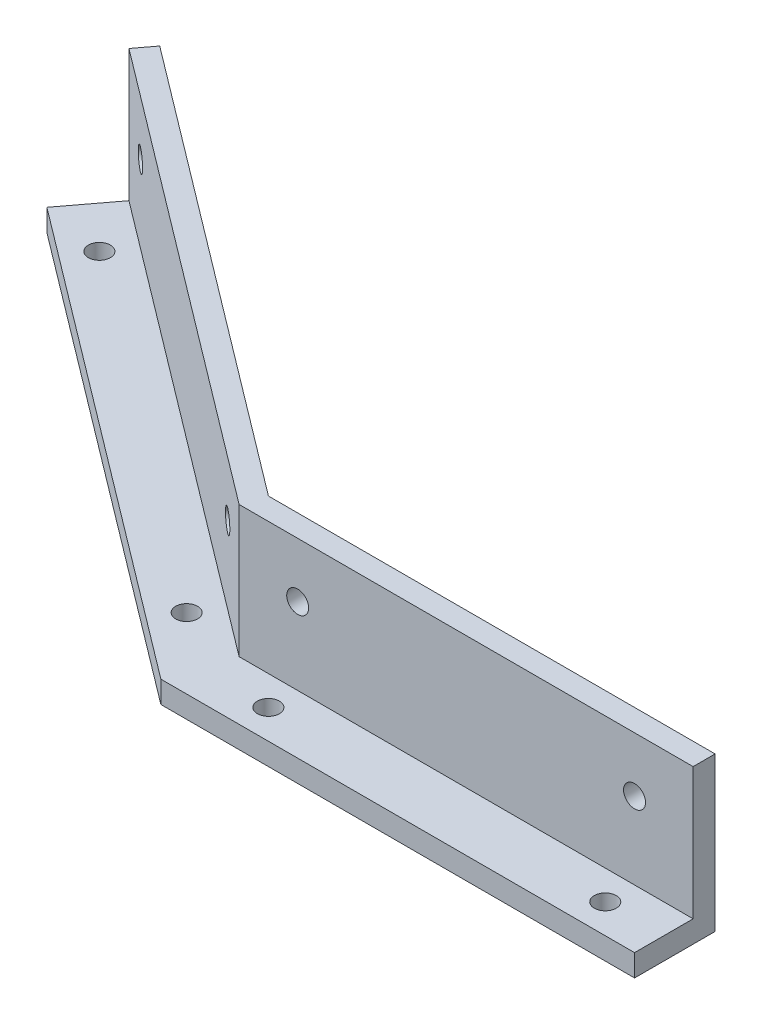
SolidWorks part; units mm, degrees
ref_plane "Alzado" through (0, 0, 0) normal (0, 0, 1) x (1, 0, 0)
ref_plane "Planta" through (0, 0, 0) normal (0, 1, 0) x (1, 0, 0)
ref_plane "Vista lateral" through (0, 0, 0) normal (1, 0, 0) x (0, 0, -1)
sketch "Croquis1" plane through (0, 0, 0) normal (0, 1, 0) x (1, 0, 0)
  line L0 (0, 0) -> (-62, 0)
  line L1 (-62, 0) -> (-123.4464, 46.4041)
  line L2 (-123.4464, 46.4041) -> (-128.2676, 40.0201)
  line L4 (0, 0) -> (0, -8)
  line L5 (0, -8) -> (-64.6814, -8)
  line L6 (-64.6814, -8) -> (-128.2676, 40.0201)
  dimension "D1" = 142.94
  dimension "D2" = 62
  dimension "D3" = 77
  dimension "D4" = 8
  dimension "D5" = 8
extrude "Saliente-Extruir4" add sketch "Croquis1" along normal blind 3
sketch "Croquis4" plane through (0, 3, 0) normal (0, 1, 0) x (1, 0, 0)
  line L0 (-123.4464, 46.4041) -> (-121.6384, 48.7981)
  line L1 (-121.6384, 48.7981) -> (-60.9945, 3)
  line L2 (-60.9945, 3) -> (0, 3)
  line L3 (0, 3) -> (0, 0)
  line L4 (-123.4464, 46.4041) -> (-128.2676, 40.0201) construction
  line L6 (-62, 0) -> (-123.4464, 46.4041) construction
  line L7 (0, 0) -> (-62, 0)
  line L8 (-62, 0) -> (-123.4464, 46.4041)
  dimension "D1" = 180
  dimension "D2" = 3
  dimension "D3" = 3
  dimension "D4" = 0
extrude "Saliente-Extruir6" add sketch "Croquis4" against normal blind 3 and the other way blind 18
sketch "Croquis5" plane through (0, 3, 0) normal (0, 1, 0) x (1, 0, 0)
  line L0 (-64.6814, -8) -> (0, -8) construction
  line L1 (0, -8) -> (0, 0) construction
  circle A0 centre (-4, -4) radius 1.5
  circle A1 centre (-58, -4) radius 1.5
  dimension "D1" = 4
  dimension "D2" = 4
  dimension "D3" = 4
  dimension "D4" = 4
extrude "Cortar-Extruir2" cut sketch "Croquis5" against normal blind 3
sketch "Croquis6" plane through (0, 3, 0) normal (0, 1, 0) x (1, 0, 0)
  line L0 (-128.2676, 40.0201) -> (-64.6814, -8) construction
  line L1 (-123.4464, 46.4041) -> (-128.2676, 40.0201) construction
  line L2 (-62, 0) -> (-64.4106, -3.192) construction
  line L3 (-64.4106, -3.192) -> (-67.6026, -0.7814) construction
  line L4 (-123.4464, 46.4041) -> (-62, 0) construction
  circle A0 centre (-122.665, 40.8015) radius 1.5
  circle A1 centre (-67.6026, -0.7814) radius 1.5
  dimension "D1" = 4
  dimension "D3" = 4
  dimension "D2" = 4
  dimension "D4" = 4
  dimension "D5" = 90
  dimension "D6" = 4
extrude "Cortar-Extruir3" cut sketch "Croquis6" against normal blind 3
sketch "Croquis7" plane through (-22.5177, 0, 29.8169) normal (-0.6027, 0, 0.798) x (0.798, 0, 0.6027)
  line L0 (-126.4763, 21) -> (-126.4763, 3) construction
  line L1 (-126.4763, 21) -> (-49.4763, 21) construction
  circle A0 centre (-118.4763, 13.5) radius 1.5
  circle A1 centre (-57.4763, 13.5) radius 1.5
  dimension "D1" = 8
  dimension "D3" = 7.5
  dimension "D5" = 3
  dimension "D2" = 7.5
  dimension "D4" = 8
extrude "Cortar-Extruir5" cut sketch "Croquis7" against normal blind 3
sketch "Croquis8" plane through (0, 0, 0) normal (0, 0, 1) x (1, 0, 0)
  line L0 (-62, 21) -> (0, 21) construction
  line L1 (0, 21) -> (0, 3) construction
  circle A0 centre (-54, 13.5) radius 1.5
  circle A1 centre (-8, 13.5) radius 1.5
  dimension "D1" = 8
  dimension "D3" = 8
  dimension "D2" = 7.5
  dimension "D4" = 7.5
extrude "Cortar-Extruir6" cut sketch "Croquis8" against normal blind 3
sketch "Croquis9" plane through (0, 3, 0) normal (0, 1, 0) x (1, 0, 0)
  line L0 (-128.2676, 40.0201) -> (-64.6814, -8) construction
  line L1 (-123.4464, 46.4041) -> (-128.2676, 40.0201) construction
  line L2 (-62, 0) -> (-64.4106, -3.192) construction
  line L3 (-64.4106, -3.192) -> (-70.7946, 1.6292) construction
  line L4 (-62, 0) -> (-123.4464, 46.4041) construction
  line L5 (0, -8) -> (0, 0) construction
  circle A0 centre (-119.4729, 38.3909) radius 1.5
  circle A1 centre (-70.7946, 1.6292) radius 1.5
  circle A2 centre (-54, -4) radius 1.5
  circle A3 centre (-8, -4) radius 1.5
  dimension "D1" = 4
  dimension "D7" = 8
  dimension "D8" = 8
  dimension "D2" = 8
  dimension "D3" = 4
  dimension "D4" = 4
  dimension "D5" = 8
  dimension "D6" = 90
extrude "Cortar-Extruir7" cut sketch "Croquis9" against normal blind 3
sketch "Croquis10" plane through (0, 3, 0) normal (0, 1, 0) x (1, 0, 0)
  circle A0 centre (-58, -4) radius 1.5
  circle A1 centre (-4, -4) radius 1.5
  circle A2 centre (-67.6026, -0.7814) radius 1.5
  circle A3 centre (-122.665, 40.8015) radius 1.5
extrude "Saliente-Extruir7" add sketch "Croquis10" against normal blind 3
